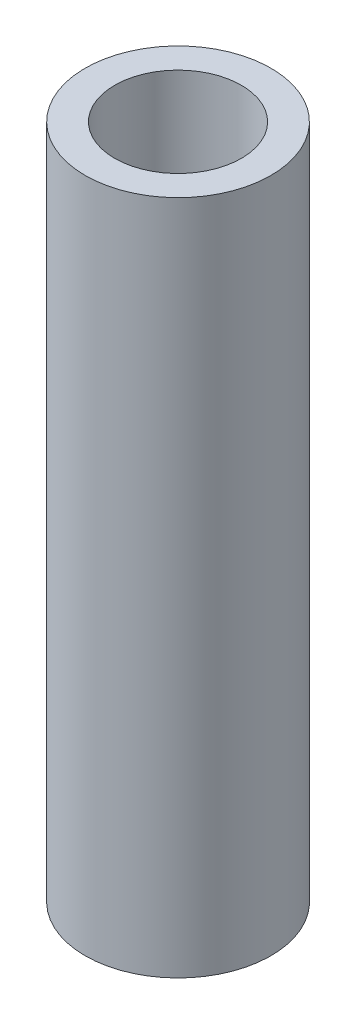
SolidWorks part; units mm, degrees
ref_plane "前基準面" through (0, 0, 0) normal (0, 0, 1) x (1, 0, 0)
ref_plane "上基準面" through (0, 0, 0) normal (0, 1, 0) x (1, 0, 0)
ref_plane "右基準面" through (0, 0, 0) normal (1, 0, 0) x (0, 0, -1)
sketch "草圖1" plane through (0, 0, 0) normal (0, 1, 0) x (1, 0, 0)
  circle A0 centre (0, 0) radius 11
  circle A1 centre (0, 0) radius 7.5
  dimension "D1" = 22
  dimension "D2" = 15
extrude "填料-伸長1" add sketch "草圖1" along normal blind 80
